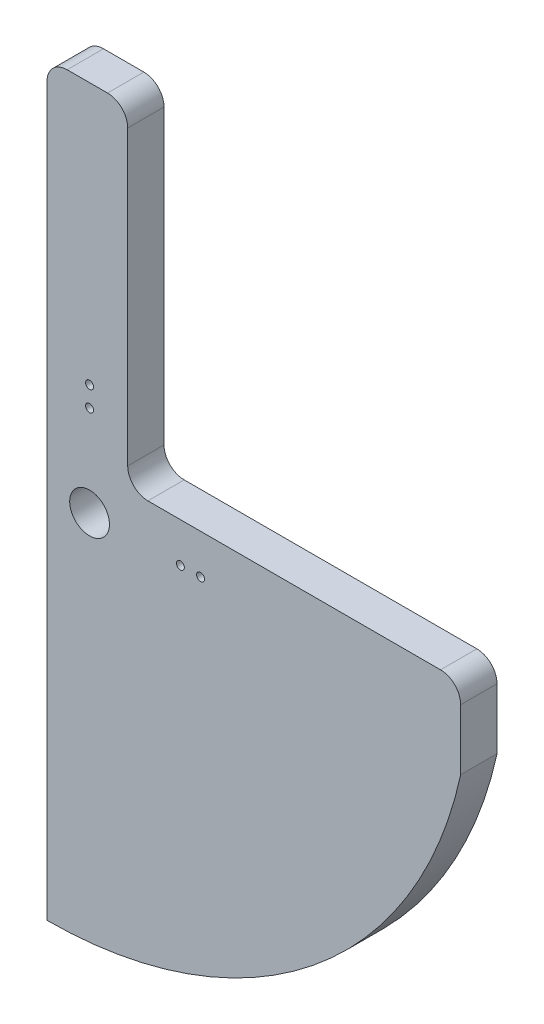
SolidWorks part; units mm, degrees
ref_plane "Front Plane" through (0, 0, 0) normal (0, 0, 1) x (1, 0, 0)
ref_plane "Top Plane" through (0, 0, 0) normal (0, 1, 0) x (1, 0, 0)
ref_plane "Right Plane" through (0, 0, 0) normal (1, 0, 0) x (0, 0, -1)
sketch "Sketch1" plane through (0, 0, 0) normal (0, 0, 1) x (1, 0, 0)
  line L2 (4.8002, 7.5301) -> (4.8002, 44.3601)
  line L6 (46.7102, -2.6299) -> (46.7102, 2.4501)
  line L7 (7.3402, 4.9901) -> (44.1702, 4.9901)
  line L11 (-2.8198, 46.9001) -> (2.2602, 46.9001)
  line L16 (46.7102, -2.6299) -> (46.7102, -5.1699)
  line L18 (-5.3598, -5.1699) -> (-5.3598, -47.0799)
  line L19 (-5.3598, 44.3601) -> (-5.3598, -5.1699)
  circle A1 centre (0, 0) radius 2.5
  arc A3 (4.8002, 7.5301) -> (7.3402, 4.9901) centre (7.3402, 7.5301) ccw
  arc A6 (44.1702, 4.9901) -> (46.7102, 2.4501) centre (44.1702, 2.4501) cw
  arc A7 (2.2602, 46.9001) -> (4.8002, 44.3601) centre (2.2602, 44.3601) cw
  arc A8 (-5.3598, 44.3601) -> (-2.8198, 46.9001) centre (-2.8198, 44.3601) cw
  circle A9 centre (0, 11.43) radius 0.5
  circle A10 centre (11.43, 0) radius 0.5
  circle A11 centre (0, 13.97) radius 0.5
  circle A12 centre (13.97, 0) radius 0.5
  arc A13 (-5.3598, -47.0799) -> (46.7102, -5.1699) centre (-5.3598, 6.2216) ccw
  point P19 (46.7102, -5.1699)
  dimension "D1" = 5
  dimension "D4" = 2.54
  dimension "D6" = 1
  dimension "D7" = 1
  dimension "D10" = 1
  dimension "D12" = 1
  dimension "D5" = 11.43
  dimension "D8" = 11.43
  dimension "D9" = 13.97
  dimension "D11" = 13.97
  dimension "D15" = 41.91
extrude "Boss-Extrude2" add sketch "Sketch1" along normal blind 4.572
